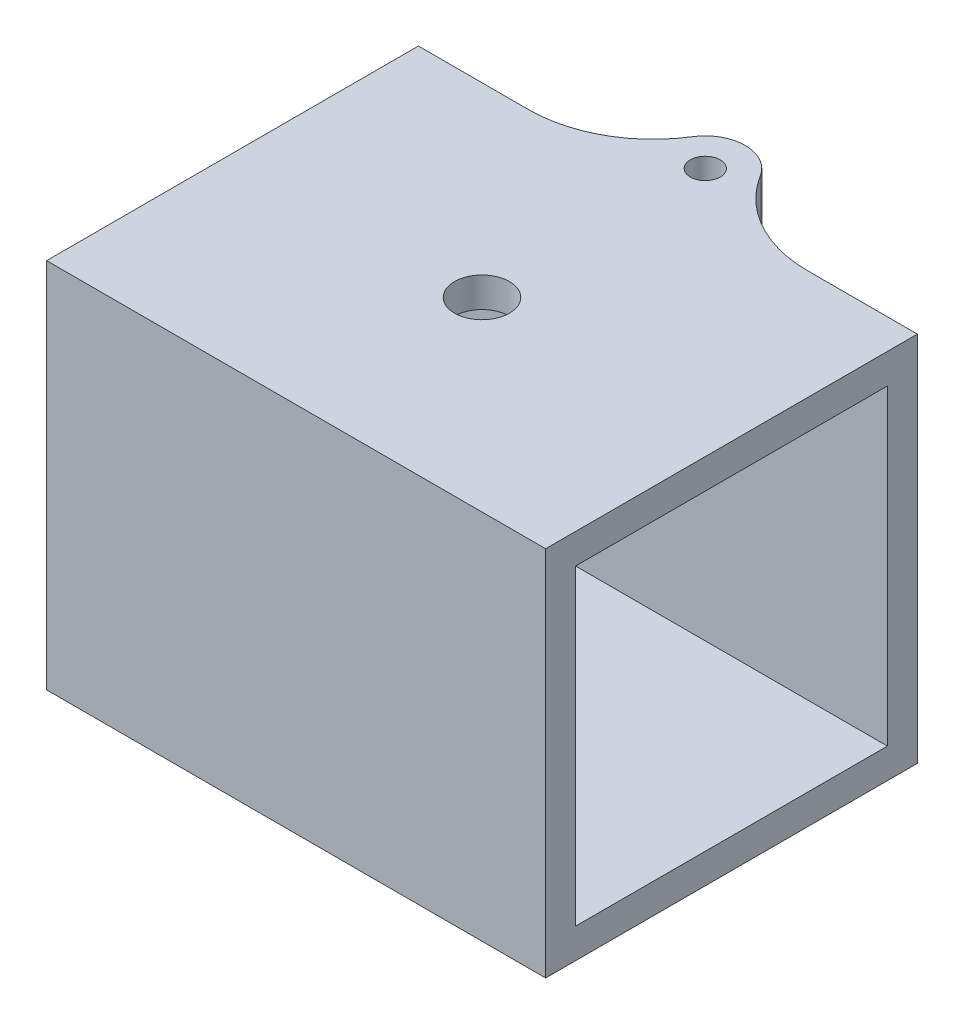
SolidWorks part; units mm, degrees
ref_plane "Front" through (0, 0, 0) normal (0, 0, 1) x (1, 0, 0)
ref_plane "Top" through (0, 0, 0) normal (0, 1, 0) x (1, 0, 0)
ref_plane "Right" through (0, 0, 0) normal (1, 0, 0) x (0, 0, -1)
sketch "Эскиз1" plane through (0, 0, 0) normal (1, 0, 0) x (0, 0, -1)
  line L1 (-12.5, -12.5) -> (12.5, -12.5)
  line L2 (-12.5, -12.5) -> (-12.5, 12.5)
  line L3 (-12.5, 12.5) -> (12.5, 12.5)
  line L4 (12.5, -12.5) -> (12.5, 12.5)
  line L5 (-12.5, -12.5) -> (12.5, 12.5) construction
  line L6 (-12.5, 12.5) -> (12.5, -12.5) construction
  point P0 (0, 0)
  dimension "D1" = 25
  dimension "D2" = 25
extrude "Вытянуть-Тонкостенный1" add sketch "Эскиз1" along normal blind 40 thin
sketch "Эскиз4" plane through (0, 14.9, 0) normal (0, 1, 0) x (1, 0, 0)
  line L0 (0, 0) -> (40, 0) construction
  line L1 (40, 14.9) -> (40, -14.9) construction
  circle A1 centre (20, 0) radius 2.2
extrude "Вырез-Вытянуть1" cut sketch "Эскиз4" against normal up to next
sketch "Эскиз7" plane through (0, -14.9, 0) normal (0, -1, 0) x (1, 0, 0)
  line L0 (40, -14.9) -> (0, -14.9) construction
  circle A0 centre (20, -17.9) radius 1.2
  circle A1 centre (20, -17.9) radius 3.2
  dimension "D1" = 3
extrude "Бобышка-Вытянуть3" add sketch "Эскиз7" against normal blind 4
sketch "Эскиз8" plane through (0, 14.9, 0) normal (0, 1, 0) x (1, 0, 0)
  circle A0 centre (20, 17.9) radius 1.2
  circle A1 centre (20, 17.9) radius 3.2
extrude "Бобышка-Вытянуть4" add sketch "Эскиз8" against normal blind 4
fillet "Скругление2" radius 10 4 edges at (21.1136, -12.9, -14.9) (18.8864, -12.9, -14.9) (21.1136, 12.9, -14.9) (18.8864, 12.9, -14.9)
